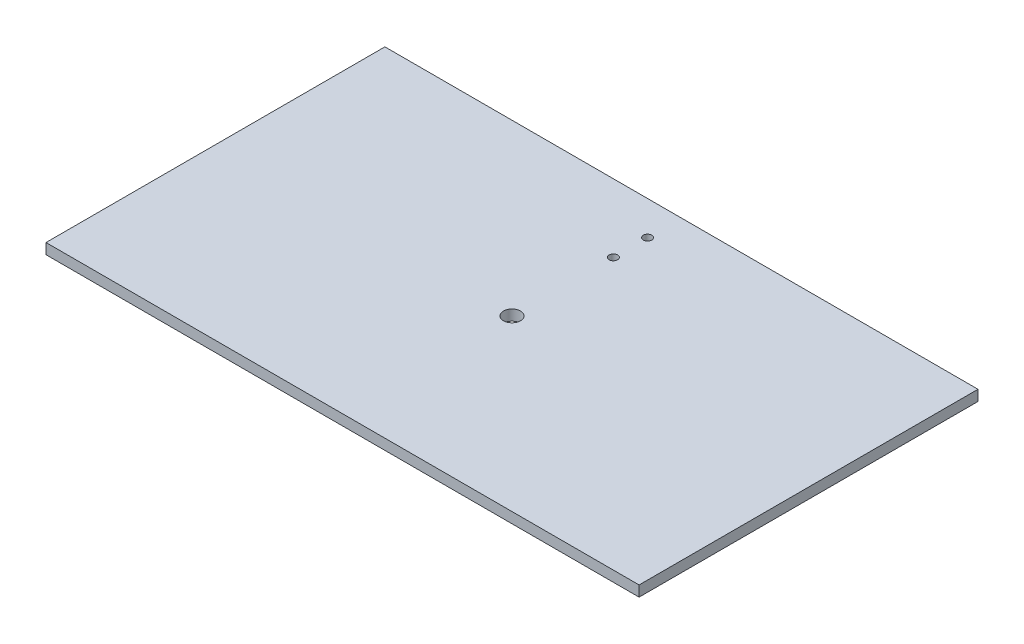
SolidWorks part; units mm, degrees
material "6061-T6 (SS)"
ref_plane "Front Plane" through (0, 0, 0) normal (0, 0, 1) x (1, 0, 0)
ref_plane "Top Plane" through (0, 0, 0) normal (0, 1, 0) x (1, 0, 0)
ref_plane "Right Plane" through (0, 0, 0) normal (1, 0, 0) x (0, 0, -1)
sketch "Sketch2" plane through (0, 0, 0) normal (0, 1, 0) x (1, 0, 0)
  line L1 (-177.8, -101.6) -> (177.8, -101.6)
  line L2 (-177.8, -101.6) -> (-177.8, 101.6)
  line L3 (-177.8, 101.6) -> (177.8, 101.6)
  line L4 (177.8, -101.6) -> (177.8, 101.6)
  line L5 (-177.8, -101.6) -> (177.8, 101.6) construction
  line L6 (-177.8, 101.6) -> (177.8, -101.6) construction
  point P0 (0, 0)
  dimension "D1" = 203.2
  dimension "D2" = 355.6
extrude "Boss-Extrude1" add sketch "Sketch2" along normal blind 6.35
sketch "Sketch3" plane through (0, 6.35, 0) normal (0, 1, 0) x (1, 0, 0)
  line L0 (0, 101.6) -> (0, -101.6) construction
  line L1 (177.8, 101.6) -> (-177.8, 101.6) construction
  line L2 (-177.8, -101.6) -> (177.8, -101.6) construction
  circle A0 centre (0, 81.28) radius 2.54
  circle A1 centre (0, 60.7799) radius 2.54
  dimension "D1" = 5.08
  dimension "D2" = 5.08
  dimension "D3" = 20.32
  dimension "D4" = 20.5001
extrude "Cut-Extrude1" cut sketch "Sketch3" against normal through all
sketch "Sketch4" plane through (0, 6.35, 0) normal (0, 1, 0) x (1, 0, 0)
  circle A0 centre (0, 0) radius 6.35
  point P0 (0, 0)
  dimension "D1" = 12.7
hole_wizard "Tap Drill for M12x1.75 Tap1" positions "Sketch4" profile "Sketch5" hole size "M12x1.75" standard "ANSI Metric"
sketch "Sketch5" plane through (0, 6.35, 0) normal (1, 0, 0) x (0, 0, 1)
  line L0 (0, 0) -> (0, 22.1144)
  line L1 (0, 22.1144) -> (5.1, 19.05)
  line L2 (5.1, 19.05) -> (5.1, 0)
  line L5 (5.1, 0) -> (0, 0)
  line L10 (0, 22.1144) -> (-5.1, 19.05) construction
  line L11 (0, -6.35) -> (0, 107.95) construction
  dimension "Hole Dia." = 10.2
  dimension "Hole Depth" = 19.05
  dimension "Drill Angle" = 118
